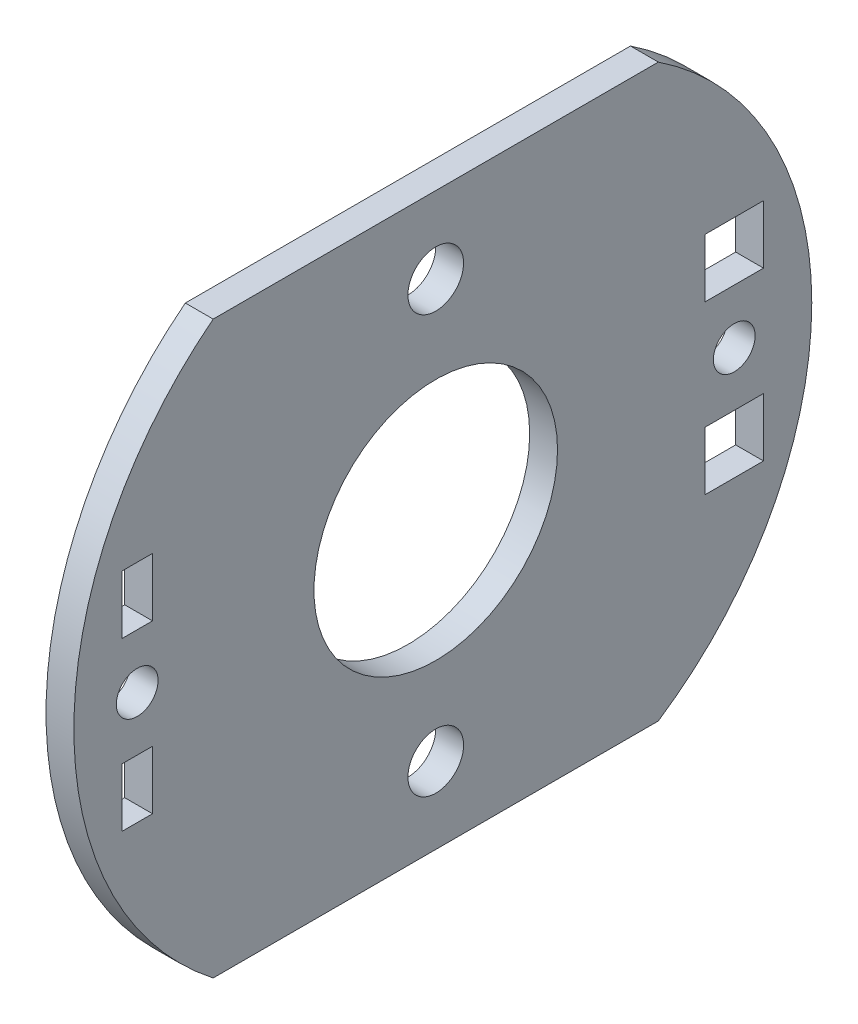
SolidWorks part; units mm, degrees
ref_plane "前视基准面" through (0, 0, 0) normal (0, 0, 1) x (1, 0, 0)
ref_plane "上视基准面" through (0, 0, 0) normal (0, 1, 0) x (1, 0, 0)
ref_plane "右视基准面" through (0, 0, 0) normal (1, 0, 0) x (0, 0, -1)
sketch "草图1" plane through (0, 0, 0) normal (1, 0, 0) x (0, 0, -1)
  line L0 (0, 0) -> (42.9, 0) construction
  line L1 (21.45, 15) -> (21.45, 26) construction
  line L2 (1.1, -3.9) -> (-1.1, -8.1) construction
  line L3 (-1.1, 3.9) -> (-1.1, 8.1)
  line L4 (-1.1, 3.9) -> (1.1, 3.9)
  line L5 (1.1, 3.9) -> (1.1, 8.1)
  line L6 (-1.1, 8.1) -> (1.1, 8.1)
  line L7 (-1.1, 3.9) -> (1.1, 8.1) construction
  line L8 (1.1, 3.9) -> (-1.1, 8.1) construction
  line L9 (-1.1, -3.9) -> (1.1, -8.1) construction
  line L10 (-1.1, -8.1) -> (1.1, -8.1)
  line L11 (1.1, -3.9) -> (1.1, -8.1)
  line L12 (-1.1, -3.9) -> (1.1, -3.9)
  line L13 (-1.1, -3.9) -> (-1.1, -8.1)
  line L14 (0, -3.9) -> (0, 3.9) construction
  line L15 (40.8, 8.1) -> (45, 3.9) construction
  line L20 (40.8, 3.9) -> (45, 8.1) construction
  line L21 (45, 3.9) -> (45, 8.1)
  line L22 (40.8, -3.9) -> (45, -3.9)
  line L27 (42.9, -3.9) -> (42.9, 3.9) construction
  line L28 (40.8, 8.1) -> (45, 8.1)
  line L29 (40.8, -3.9) -> (40.8, -8.1)
  line L30 (40.8, -8.1) -> (45, -8.1)
  line L31 (45, -3.9) -> (45, -8.1)
  line L32 (40.8, -3.9) -> (45, -8.1) construction
  line L33 (40.8, -8.1) -> (45, -3.9) construction
  line L34 (40.8, 3.9) -> (40.8, 8.1)
  line L35 (40.8, 3.9) -> (45, 3.9)
  line L36 (21.45, -15) -> (21.45, -26) construction
  line L37 (21.45, -20.5) -> (37.4422, -20.5)
  line L38 (21.45, -20.5) -> (5.4578, -20.5)
  line L39 (21.45, 20.5) -> (37.4422, 20.5)
  line L40 (21.45, 20.5) -> (5.4578, 20.5)
  line L41 (21.45, 0) -> (21.45, 10.8777) construction
  circle A10 centre (21.45, 0) radius 15 construction
  circle A11 centre (21.45, 15) radius 2
  circle A12 centre (21.45, -15) radius 2
  circle A13 centre (21.45, 0) radius 8.75
  circle A15 centre (0, 0) radius 1.5
  circle A16 centre (42.9, 0) radius 1.5
  circle A17 centre (21.45, 0) radius 26 construction
  arc A18 (5.4578, -20.5) -> (5.4578, 20.5) centre (21.45, 0) cw
  arc A20 (37.4422, 20.5) -> (37.4422, -20.5) centre (23.8992, 0) cw
  point P2 (42.9, 0)
  point P11 (0, 0)
  point P16 (0, 6)
  point P23 (0, -6)
  point P34 (42.9, 6)
  point P38 (42.9, -6)
extrude "凸台-拉伸1" add sketch "草图1" along normal blind 2
